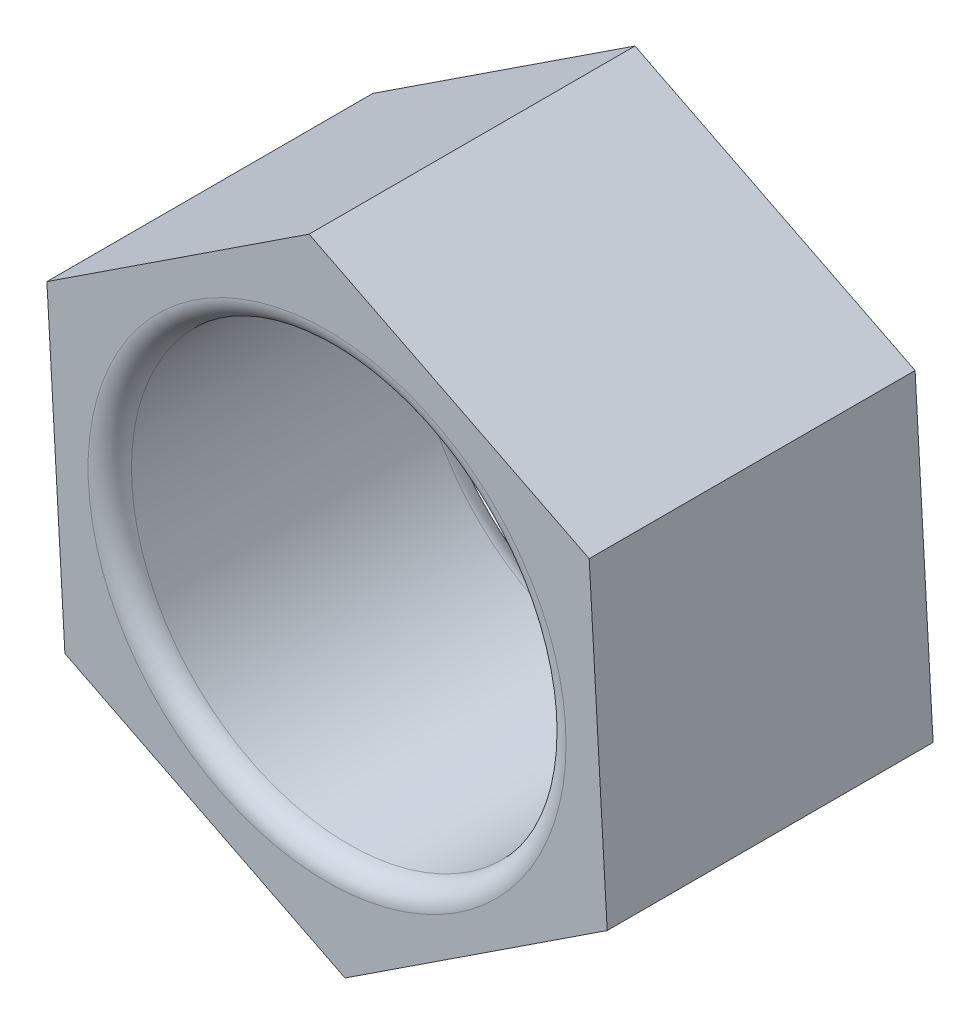
SolidWorks part; units mm, degrees
ref_plane "Front Plane" through (0, 0, 0) normal (0, 0, 1) x (1, 0, 0)
ref_plane "Top Plane" through (0, 0, 0) normal (0, 1, 0) x (1, 0, 0)
ref_plane "Right Plane" through (0, 0, 0) normal (1, 0, 0) x (0, 0, -1)
sketch "Sketch1" plane through (0, 0, 0) normal (0, 0, 1) x (1, 0, 0)
  line L1 (-0.0829, 1.441) -> (-1.2894, 0.6487)
  line L2 (-1.2894, 0.6487) -> (-1.2065, -0.7923)
  line L3 (-1.2065, -0.7923) -> (0.0829, -1.441)
  line L4 (0.0829, -1.441) -> (1.2894, -0.6487)
  line L5 (1.2894, -0.6487) -> (1.2065, 0.7923)
  line L6 (1.2065, 0.7923) -> (-0.0829, 1.441)
  circle A0 centre (0, 0) radius 1.25 construction
  dimension "D1" = 2.5
extrude "Boss-Extrude1" add sketch "Sketch1" along normal blind 1.5
sketch "Sketch2" plane through (0, 0, 1.5) normal (0, 0, 1) x (1, 0, 0)
  circle A0 centre (0, 0) radius 1
  dimension "D1" = 2
extrude "Cut-Extrude1" cut sketch "Sketch2" against normal through all both and the other way through all
fillet "Fillet1" radius 0.1 2 edges at (1, 0, 0) (1, 0, 1.5)
